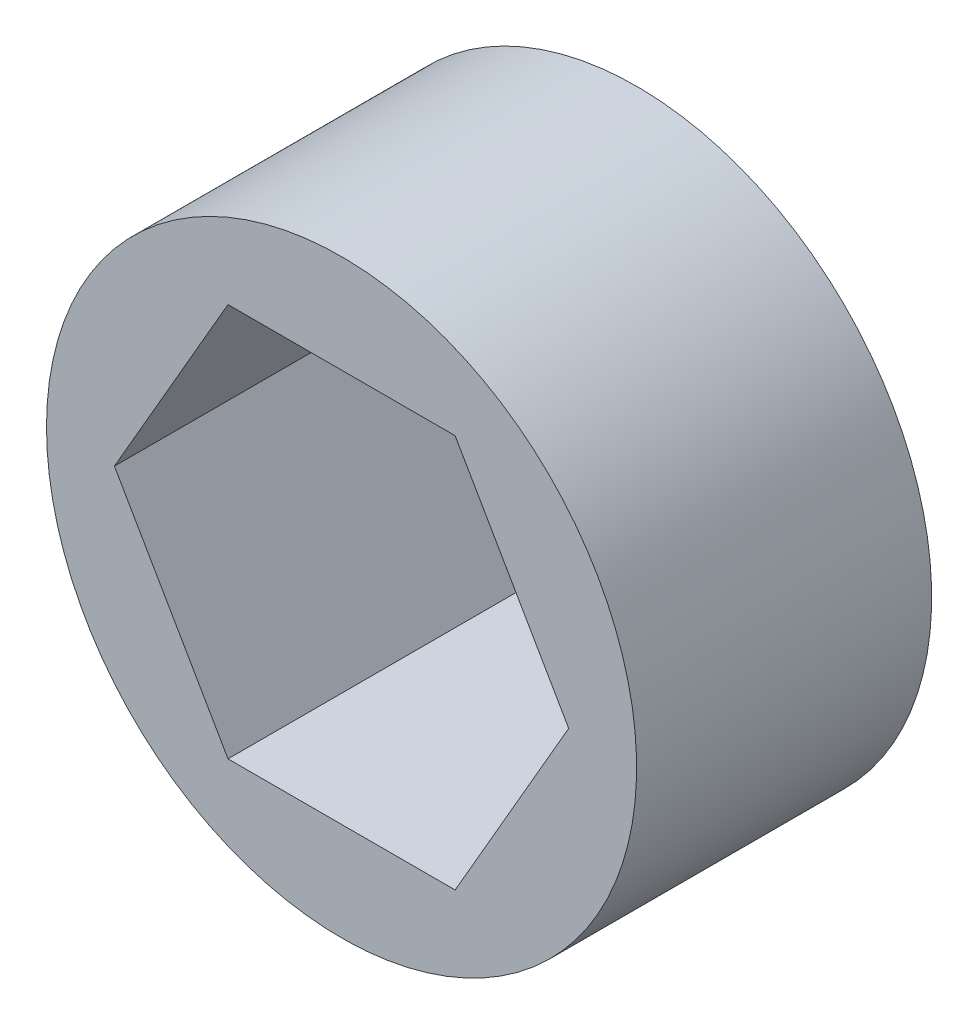
SolidWorks part; units mm, degrees
material "PET"
ref_plane "Front Plane" through (0, 0, 0) normal (0, 0, 1) x (1, 0, 0)
ref_plane "Top Plane" through (0, 0, 0) normal (0, 1, 0) x (1, 0, 0)
ref_plane "Right Plane" through (0, 0, 0) normal (1, 0, 0) x (0, 0, -1)
sketch "Sketch1" plane through (0, 0, 0) normal (0, 0, 1) x (1, 0, 0)
  line L1 (7.3323, 0) -> (3.6662, 6.35)
  line L2 (3.6662, 6.35) -> (-3.6662, 6.35)
  line L3 (-3.6662, 6.35) -> (-7.3323, 0)
  line L4 (-7.3323, 0) -> (-3.6662, -6.35)
  line L5 (-3.6662, -6.35) -> (3.6662, -6.35)
  line L6 (3.6662, -6.35) -> (7.3323, 0)
  circle A1 centre (0, 0) radius 6.35 construction
  circle A2 centre (0, 0) radius 9.525
  dimension "D1" = 12.7
  dimension "D2" = 19.05
extrude "Boss-Extrude1" add sketch "Sketch1" along normal blind 9.525 contours L5 L6 L1 L2 L3 L4 | A2
